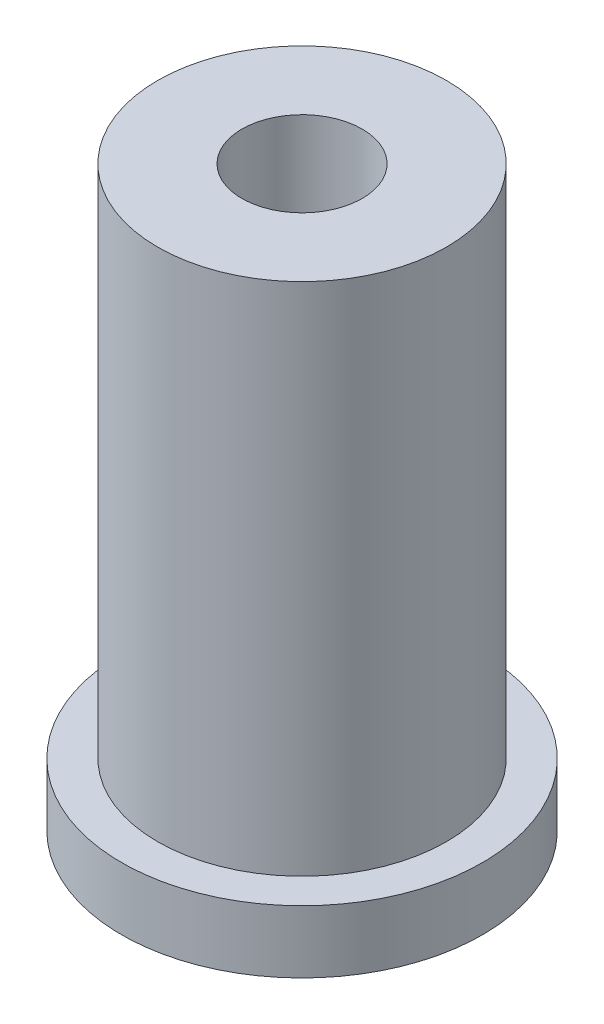
SolidWorks part; units mm, degrees
ref_plane "Front Plane" through (0, 0, 0) normal (0, 0, 1) x (1, 0, 0)
ref_plane "Top Plane" through (0, 0, 0) normal (0, 1, 0) x (1, 0, 0)
ref_plane "Right Plane" through (0, 0, 0) normal (1, 0, 0) x (0, 0, -1)
sketch "Sketch1" plane through (0, 0, 0) normal (0, 1, 0) x (1, 0, 0)
  circle A0 centre (0, 0) radius 4.7625
  dimension "D1" = 9.525
extrude "Boss-Extrude1" add sketch "Sketch1" along normal blind 1.651
sketch "Sketch2" plane through (0, 1.651, 0) normal (0, 1, 0) x (1, 0, 0)
  circle A0 centre (0, 0) radius 3.81
  dimension "D1" = 7.62
extrude "Boss-Extrude2" add sketch "Sketch2" along normal blind 13.589
sketch "Sketch3" plane through (0, 0, 0) normal (0, -1, 0) x (1, 0, 0)
  circle A0 centre (0, 0) radius 1.5875
  dimension "D1" = 3.175
extrude "Cut-Extrude2" cut sketch "Sketch3" against normal through all
